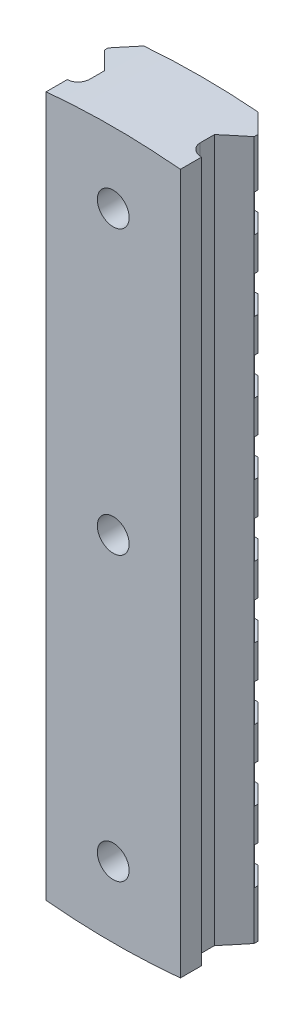
SolidWorks part; units mm, degrees
ref_plane "Front Plane" through (0, 0, 0) normal (0, 0, 1) x (1, 0, 0)
ref_plane "Top Plane" through (0, 0, 0) normal (0, 1, 0) x (1, 0, 0)
ref_plane "Right Plane" through (0, 0, 0) normal (1, 0, 0) x (0, 0, -1)
sketch "Sketch1" plane through (0, 0, 0) normal (0, 1, 0) x (1, 0, 0)
  line L0 (0, 0) -> (0, 14.7477) construction
  line L1 (-8.07, 12.4) -> (8.07, 12.4)
  line L2 (8.07, 12.4) -> (10.6, 9.87)
  line L3 (10.6, 9.87) -> (10.6, 9.33)
  line L4 (10.6, 9.33) -> (7.8, 6.53)
  line L5 (7.8, 6.53) -> (7.8, 4.5)
  line L6 (9.3, 3) -> (9.5, 3)
  line L7 (9.5, 3) -> (9.5, 0)
  line L8 (9.5, 0) -> (-9.5, 0)
  line L9 (-9.5, 0) -> (-9.5, 3)
  line L10 (-9.5, 3) -> (-9.3, 3)
  line L11 (-7.8, 4.5) -> (-7.8, 6.53)
  line L12 (-7.8, 6.53) -> (-10.6, 9.33)
  line L13 (-10.6, 9.33) -> (-10.6, 9.87)
  line L14 (-10.6, 9.87) -> (-8.07, 12.4)
  line L16 (-9.5, 10.97) -> (9.5, 10.97) construction
  line L17 (-9.5, 10.97) -> (-9.5, 8.23) construction
  line L18 (-9.5, 8.23) -> (9.5, 8.23) construction
  line L19 (9.5, 10.97) -> (9.5, 8.23) construction
  arc A0 (7.8, 4.5) -> (9.3, 3) centre (9.3, 4.5) ccw
  arc A1 (-9.3, 3) -> (-7.8, 4.5) centre (-9.3, 4.5) ccw
  dimension "D8" = 1.5
  dimension "D2" = 21.2
  dimension "D3" = 19
  dimension "D4" = 45
  dimension "D5" = 2.74
  dimension "D6" = 4.17
  dimension "D7" = 15.6
  dimension "D9" = 9.4
  dimension "D10" = 3
  dimension "D11" = 19
  dimension "D12" = 90
extrude "Boss-Extrude1" add sketch "Sketch1" along normal mid plane 100
sketch "Sketch2" plane through (0, 0, 0) normal (1, 0, 0) x (0, 0, -1)
  line L0 (0, 0) -> (19.6368, 0) construction
  line L1 (12.4, 50) -> (12.4, -50) construction
  line L2 (14.4, 2.625) -> (9.4, 2.625)
  line L3 (14.4, 2.625) -> (14.4, -2.625)
  line L4 (14.4, -2.625) -> (9.4, -2.625)
  line L5 (9.4, 2.625) -> (9.4, -2.625)
  dimension "D1" = 5.25
  dimension "D2" = 3
  dimension "D3" = 5
extrude "Cut-Extrude1" cut sketch "Sketch2" against normal mid plane 100
pattern_linear "LPattern1" count 5 spacing 10 along (0, 1, 0) count 5 spacing 10 along (0, -1, 0) of "Cut-Extrude1"
sketch "Sketch3" plane through (0, 0, 0) normal (0, 0, 1) x (1, 0, 0)
  line L0 (0, 0) -> (0, 64.9591) construction
  line L1 (0, 0) -> (43.3608, 0) construction
  line L2 (-15, 48.8686) -> (-15, -48.8686)
  line L3 (15, 48.8686) -> (15, -48.8686)
  arc A0 (-15, 48.8686) -> (15, 48.8686) centre (0, -50) cw
  arc A1 (-15, -48.8686) -> (15, -48.8686) centre (0, 50) ccw
  dimension "D3" = 100
  dimension "D1" = 30
  dimension "D2" = 50
extrude "Cut-Extrude2" cut sketch "Sketch3" against normal mid plane 100 flip side to cut
hole_wizard "CBORE for M4 Hex Socket Head Cap Screw1" positions "Sketch5" profile "Sketch7" counterbore size "M4" standard "DIN" end condition through all
sketch "Sketch5" plane through (0, 0, -12.4) normal (0, 0, -1) x (-1, 0, 0)
  line L0 (0, 0) -> (0, 62.5862) construction
  line L3 (0, 0) -> (32.774, 0) construction
  point P0 (0, 40)
  point P2 (0, -40)
  point P5 (0, 0)
  dimension "D1" = 80
sketch "Sketch7" plane through (0, 40, -12.4) normal (1, 0, 0) x (0, 1, 0)
  line L0 (0, 0) -> (0, 12.4)
  line L1 (0, 12.4) -> (2.25, 12.4)
  line L3 (2.25, 12.4) -> (2.25, 4.4)
  line L4 (2.25, 4.4) -> (4, 4.4)
  line L5 (4, 4.4) -> (4, 0)
  line L7 (4, 0) -> (0, 0)
  line L11 (0, -6.35) -> (0, 107.95) construction
  dimension "Thru Hole Dia." = 4.5
  dimension "Thru Hole Depth" = 12.4
  dimension "C'Bore Dia." = 8
  dimension "C'Bore Depth" = 4.4
